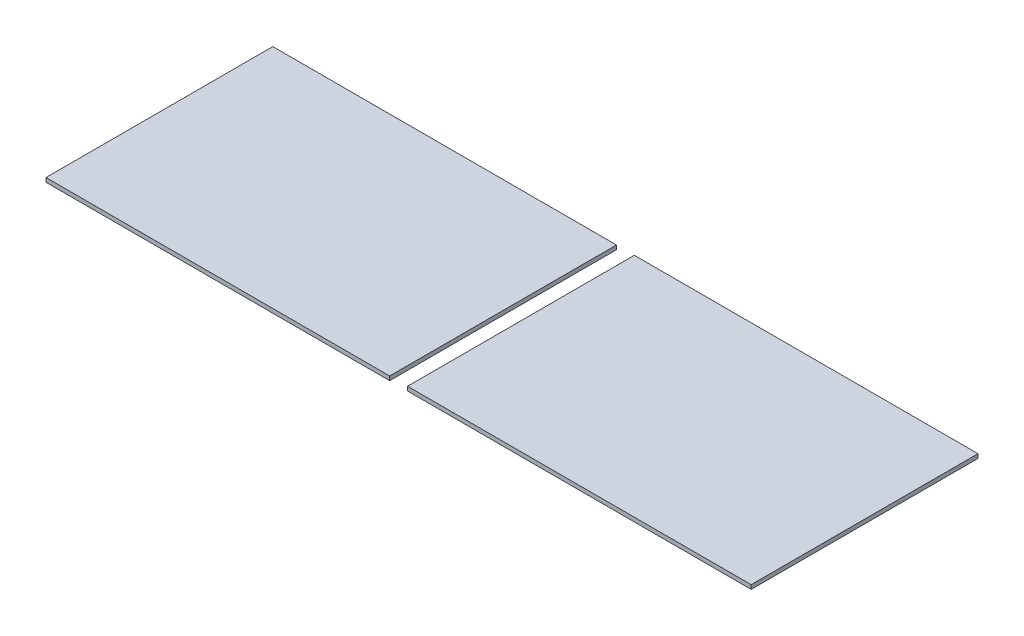
SolidWorks part; units mm, degrees
material "PE High Density"
ref_plane "Front Plane" through (0, 0, 0) normal (0, 0, 1) x (1, 0, 0)
ref_plane "Top Plane" through (0, 0, 0) normal (0, 1, 0) x (1, 0, 0)
ref_plane "Right Plane" through (0, 0, 0) normal (1, 0, 0) x (0, 0, -1)
sketch "Sketch1" plane through (0, 0, 0) normal (0, 1, 0) x (1, 0, 0)
  line L0 (12.9939, 165) -> (512.9939, 165)
  line L1 (12.9939, 165) -> (12.9939, -165)
  line L2 (512.9939, 165) -> (512.9939, -165)
  line L3 (12.9939, -165) -> (512.9939, -165)
  line L4 (12.9939, 165) -> (512.9939, -165) construction
  line L5 (512.9939, 165) -> (12.9939, -165) construction
  point P1 (0, 0)
  dimension "D1" = 500
  dimension "D2" = 330
extrude "Boss-Extrude1" add sketch "Sketch1" along normal blind 6
mirror "Mirror1" about plane through (0, 0, 0) normal (1, 0, 0) of bodies 101
